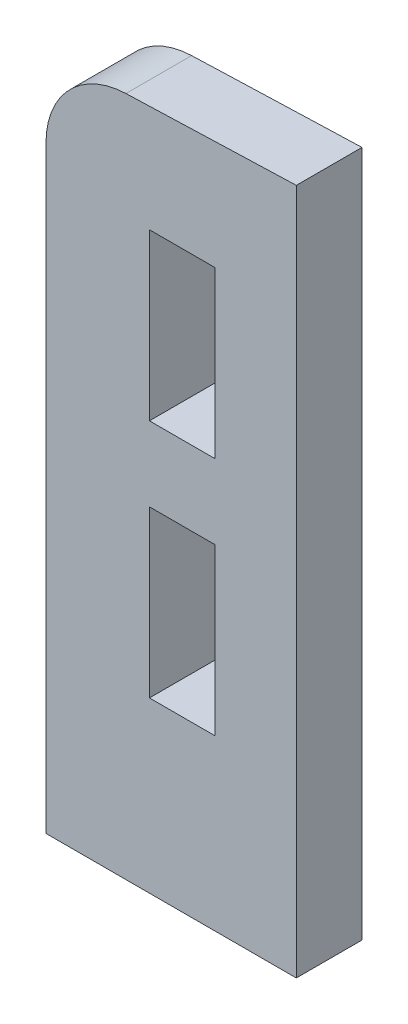
SolidWorks part; units mm, degrees
ref_plane "Front Plane" through (0, 0, 0) normal (0, 0, 1) x (1, 0, 0)
ref_plane "Top Plane" through (0, 0, 0) normal (0, 1, 0) x (1, 0, 0)
ref_plane "Right Plane" through (0, 0, 0) normal (1, 0, 0) x (0, 0, -1)
sketch "Sketch1" plane through (0, 0, 0) normal (0, 0, 1) x (1, 0, 0)
  line L1 (-26.416, -9.8) -> (26.416, -9.8)
  line L2 (-26.416, -9.8) -> (-26.416, 9.8)
  line L3 (-26.416, 9.8) -> (26.416, 9.8)
  line L4 (26.416, -9.8) -> (26.416, 9.8)
  line L5 (-26.416, -9.8) -> (26.416, 9.8) construction
  line L6 (-26.416, 9.8) -> (26.416, -9.8) construction
  line L7 (-20.15, -9.8) -> (20.15, -9.8)
  line L8 (-20.15, -9.8) -> (-20.15, 9.8)
  line L9 (-20.15, 9.8) -> (20.15, 9.8)
  line L10 (20.15, -9.8) -> (20.15, 9.8)
  line L11 (-20.15, -9.8) -> (20.15, 9.8) construction
  line L12 (-20.15, 9.8) -> (20.15, -9.8) construction
  line L13 (-26.416, 9.8) -> (26.416, 9.8)
  line L14 (-26.416, 9.8) -> (-26.416, 14.8)
  line L15 (-26.416, 14.8) -> (26.416, 14.8)
  line L16 (26.416, 9.8) -> (26.416, 14.8)
  line L17 (26.416, -9.8) -> (-26.416, -9.8)
  line L18 (26.416, -9.8) -> (26.416, -14.8)
  line L19 (26.416, -14.8) -> (-26.416, -14.8)
  line L20 (-26.416, -9.8) -> (-26.416, -14.8)
  circle A0 centre (-23.95, -4.974) radius 1.675
  circle A1 centre (-23.95, 4.974) radius 1.675
  circle A2 centre (23.95, 4.974) radius 1.675
  circle A3 centre (23.95, -4.974) radius 1.675
  point P0 (0, 0)
  point P14 (0, 0)
  dimension "D1" = 3.35
  dimension "D2" = 3.35
  dimension "D3" = 3.35
  dimension "D4" = 3.35
  dimension "D7" = 4.826
  dimension "D8" = 3.8
  dimension "D9" = 3.8
  dimension "D10" = 4.826
  dimension "D11" = 4.826
  dimension "D12" = 4.826
  dimension "D13" = 3.8
  dimension "D5" = 19.6
  dimension "D6" = 52.832
  dimension "D15" = 40.3
  dimension "D16" = 5
  dimension "D17" = 5
  dimension "3.9" = 3.8
extrude "Boss-Extrude2" add sketch "Sketch1" along normal blind 3.175 contours L1 L8 L3 L2 A1 A0 | L10 L1 L4 L3 A3 A2 | L14 L13 L16 L15 | L18 L17 L20 L19
sketch "Sketch3" plane through (0, 0, 3.175) normal (0, 0, 1) x (1, 0, 0)
  line L0 (26.416, -14.8) -> (56.416, -14.8)
  line L6 (26.416, 14.8) -> (56.416, 14.8)
  line L7 (26.416, 14.8) -> (26.416, -14.906)
  line L8 (26.416, -14.906) -> (56.416, -14.906)
  line L9 (56.416, 14.8) -> (56.416, -14.906)
  line M3 (26.416, -14.8) -> (26.416, 14.8)
  dimension "D2" = 30
extrude "Boss-Extrude3" add sketch "Sketch3" against normal up to surface (3.175 mm away) contours L9 L6 L0 M3 up to face at (0, 0, 0)
sketch "Sketch4" plane through (0, 0, 0) normal (0, 0, -1) x (-1, 0, 0)
  line L3 (-56.416, 14.8) -> (-56.416, -14.8) construction
  line L4 (-56.416, -14.8) -> (26.416, -14.8) construction
  circle A0 centre (-40.576, 7.77) radius 4.85
  dimension "D1" = 15.84
  dimension "D2" = 22.57
  dimension "D3" = 9.7
extrude "Cut-Extrude1" cut sketch "Sketch4" against normal blind 10 contours A0
sketch "Sketch22" plane through (0, 0, 0) normal (0, 0, -1) x (-1, 0, 0)
  line L0 (-52.3294, 14.8) -> (-30.0917, 14.8)
  line L1 (26.416, 14.8) -> (-56.416, 14.8) construction
  circle A0 centre (-40.576, 7.77) radius 9.175
  dimension "D1" = 18.35
extrude "Boss-Extrude14" add sketch "Sketch22" against normal up to surface (3.175 mm away) contours L0 A0
sketch "Sketch23" plane through (0, 0, 0) normal (0, 0, -1) x (-1, 0, 0)
  line L0 (-49.751, 7.77) -> (-49.751, -14.8)
  line L1 (-56.416, -14.8) -> (26.416, -14.8) construction
  circle A0 centre (-40.576, 7.77) radius 9.175
  line M4 (-46.4717, 14.8) -> (-56.416, 14.8)
  line M5 (-56.416, 14.8) -> (-56.416, -14.8)
  line M6 (-56.416, -14.8) -> (26.416, -14.8)
extrude "Cut-Extrude8" cut sketch "Sketch23" against normal blind 10 contours A0 L0 M4 M5 M6
sketch "Sketch24" plane through (0, 0, 0) normal (0, 0, -1) x (-1, 0, 0)
  line L0 (25.625, 4.974) -> (25.625, 17.1862)
  line L1 (21.4452, -14.8) -> (27.751, -14.8)
  line L2 (-49.751, -14.8) -> (26.416, -14.8) construction
  line L3 (26.416, 14.8) -> (-34.6803, 14.8) construction
  line L4 (25.625, 14.8) -> (30.625, 14.8)
  line L5 (25.625, 14.8) -> (25.625, -14.8)
  line L6 (25.625, -14.8) -> (30.625, -14.8)
  line L7 (30.625, 14.8) -> (30.625, -14.8)
  circle A0 centre (23.95, 4.974) radius 1.675 construction
  line M14 (26.416, -14.8) -> (26.416, 14.8)
  dimension "D1" = 5
extrude "Boss-Extrude15" add sketch "Sketch24" against normal up to surface (3.175 mm away) contours L7 L4 L1 L6 M14 up to face at (45.426, 7.77, 3.175)
sketch "Sketch25" plane through (0, 0, 0) normal (0, 0, -1) x (-1, 0, 0)
  line L0 (30.625, 14.8) -> (30.625, -14.8) construction
  line L1 (30.625, 9.8) -> (33.8, 9.8)
  line L2 (30.625, 9.8) -> (30.625, 1.8)
  line L3 (30.625, 1.8) -> (33.8, 1.8)
  line L4 (33.8, 9.8) -> (33.8, 1.8)
  line L5 (28.9462, -14.8) -> (31.8791, -14.8)
  line L6 (30.625, -1.8) -> (33.8, -1.8)
  line L7 (30.625, -1.8) -> (30.625, -9.8)
  line L8 (30.625, -9.8) -> (33.8, -9.8)
  line L9 (33.8, -1.8) -> (33.8, -9.8)
  line L10 (-49.751, -14.8) -> (30.625, -14.8) construction
  line L12 (30.625, 14.8) -> (38.8, 14.8)
  line L13 (30.625, 14.8) -> (30.625, -14.8)
  line L14 (30.625, -14.8) -> (38.8, -14.8)
  line L15 (38.8, 14.8) -> (38.8, -14.8)
  line M23 (30.625, -14.8) -> (30.625, 14.8)
  dimension "D1" = 3.175
  dimension "D2" = 3.175
  dimension "D3" = 8
  dimension "D4" = 8
  dimension "D5" = 5
  dimension "D6" = 0
  dimension "D7" = 8.175
  dimension "D8" = 5
extrude "Boss-Extrude16" add sketch "Sketch25" against normal up to surface (3.175 mm away) contours L15 L12 L1 L4 L3 L6 L9 L8 L5 L14 M23 up to face at (45.426, 7.77, 3.175)
sketch "Sketch26" plane through (0, 0, 0) normal (0, 0, -1) x (-1, 0, 0)
  line L0 (-34.6803, 14.8) -> (38.8, 14.8)
  arc A0 (-40.576, 16.945) -> (38.8, 14.8) centre (-135.5308, -4966.6007) cw
  arc A1 (-34.6803, 14.8) -> (-49.751, 7.77) centre (-40.576, 7.77) ccw construction
  circle A2 centre (-40.576, 7.77) radius 9.175
  arc M18 (-34.6803, 14.8) -> (-49.751, 7.77) centre (-40.576, 7.77) ccw
  line M22 (38.8, 14.8) -> (-34.6803, 14.8)
extrude "Boss-Extrude17" add sketch "Sketch26" against normal up to surface (3.175 mm away) contours A0 M18 M22 up to face at (-32.2125, 5.8, 3.175)
fillet "Fillet5" radius 4 1 edges at (-38.8, 14.8, 1.5875)
sketch "Sketch27" plane through (0, 0, 0) normal (0, 0, -1) x (-1, 0, 0)
  line L0 (-49.751, -14.8) -> (38.8, -14.8) construction
  line L1 (-44.751, -9.8) -> (-41.576, -9.8)
  line L2 (-44.751, -9.8) -> (-44.751, -1.8)
  line L3 (-44.751, -1.8) -> (-41.576, -1.8)
  line L4 (-41.576, -9.8) -> (-41.576, -1.8)
  line L5 (-49.751, 7.77) -> (-49.751, -14.8) construction
  dimension "D1" = 3.175
  dimension "D2" = 8
  dimension "D3" = 5
  dimension "D4" = 5
extrude "Cut-Extrude9" cut sketch "Sketch27" against normal blind 10
sketch "Sketch28" plane through (0, 0, 0) normal (0, 0, -1) x (-1, 0, 0)
  line L0 (-49.751, -14.8) -> (38.8, -14.8) construction
  line L1 (-49.751, -14.8) -> (-31.751, -14.8)
  line L2 (-49.751, -14.8) -> (-49.751, -17.975)
  line L3 (-49.751, -17.975) -> (-31.751, -17.975)
  line L4 (-31.751, -14.8) -> (-31.751, -17.975)
  line L5 (-14.45, -14.8) -> (3.55, -14.8)
  line L6 (-14.45, -14.8) -> (-14.45, -17.975)
  line L7 (-14.45, -17.975) -> (3.55, -17.975)
  line L8 (3.55, -14.8) -> (3.55, -17.975)
  line L9 (38.8, 10.936) -> (38.8, -14.8) construction
  line L10 (20.8, -14.8) -> (38.8, -14.8)
  line L11 (20.8, -14.8) -> (20.8, -17.975)
  line L12 (20.8, -17.975) -> (38.8, -17.975)
  line L13 (38.8, -14.8) -> (38.8, -17.975)
  dimension "D1" = 3.175
  dimension "D2" = 3.175
  dimension "D3" = 3.175
  dimension "D4" = 18
  dimension "D5" = 18
  dimension "D6" = 18
  dimension "D7" = 0
  dimension "D8" = 17.25
extrude "Boss-Extrude18" add sketch "Sketch28" against normal up to surface (3.175 mm away) contours L2 L1 L4 L3 | L6 L5 L8 L7 | L11 L10 L13 L12 up to face at (43.1635, -5.8, 3.175)
sketch "Sketch29" plane through (0, 0, 0) normal (0, 0, -1) x (-1, 0, 0)
  line L0 (23.95, 4.974) -> (26.7, 4.974)
  line L2 (26.7, 17.4371) -> (-53.9805, 17.4371)
  line L3 (26.7, 17.4371) -> (26.7, -24.164)
  line L4 (26.7, -24.164) -> (-53.9805, -24.164)
  line L5 (-53.9805, 17.4371) -> (-53.9805, -24.164)
  dimension "D1" = 2.75
extrude "Cut-Extrude10" cut sketch "Sketch29" against normal through all both
